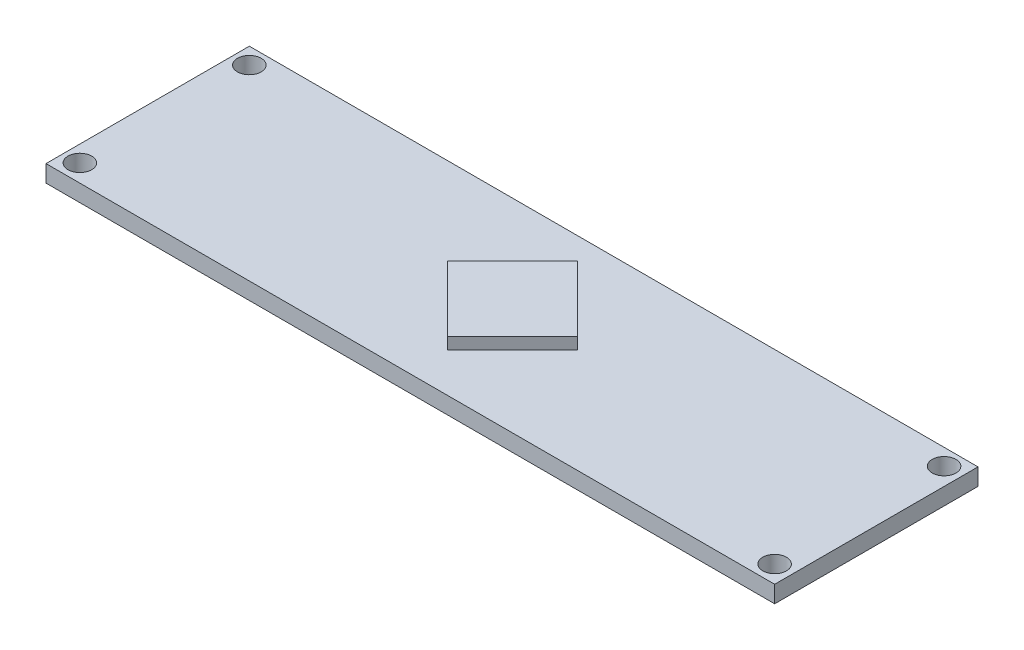
SolidWorks part; units mm, degrees
ref_plane "Front Plane" through (0, 0, 0) normal (0, 0, 1) x (1, 0, 0)
ref_plane "Top Plane" through (0, 0, 0) normal (0, 1, 0) x (1, 0, 0)
ref_plane "Right Plane" through (0, 0, 0) normal (1, 0, 0) x (0, 0, -1)
sketch "Sketch1" plane through (0, 0, 0) normal (0, 1, 0) x (1, 0, 0)
  line L0 (0, 2.9321) -> (0, -2.8615) construction
  line L1 (-5.5703, 0) -> (5.0885, 0) construction
  line L3 (-21.5, 6) -> (21.5, 6)
  line L4 (-21.5, 6) -> (-21.5, -6)
  line L5 (-21.5, -6) -> (21.5, -6)
  line L6 (21.5, 6) -> (21.5, -6)
  circle A0 centre (-20.5344, -4.967) radius 0.7
  circle A1 centre (20.4656, -4.967) radius 0.7
  circle A2 centre (20.4656, 5.033) radius 0.7
  circle A3 centre (-20.5344, 5.033) radius 0.7
  dimension "D3" = 2
  dimension "D4" = 2
  dimension "D1" = 43
  dimension "D2" = 12
extrude "Boss-Extrude1" add sketch "Sketch1" along normal blind 1
sketch "Sketch3" plane through (0, 1, 0) normal (0, 1, 0) x (1, 0, 0)
  line L1 (-3.9809, 0.1599) -> (-0.1314, 4.0094)
  line L2 (-3.9809, 0.1599) -> (-0.1314, -3.6897)
  line L3 (-0.1314, -3.6897) -> (3.7182, 0.1599)
  line L4 (-0.1314, 4.0094) -> (3.7182, 0.1599)
extrude "Boss-Extrude2" add sketch "Sketch3" along normal blind 0.7
